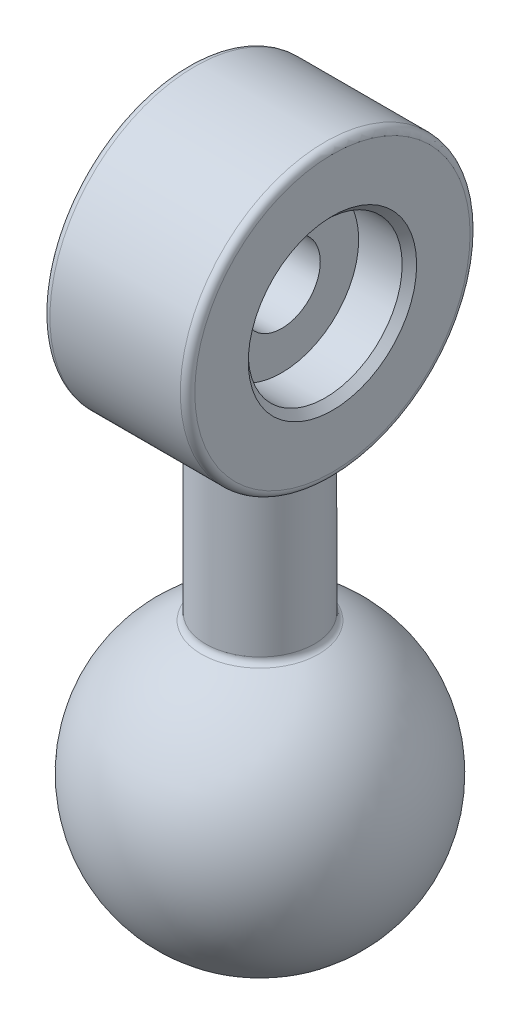
SolidWorks part; units mm, degrees
material "ABS"
ref_plane "Front Plane" through (0, 0, 0) normal (0, 0, 1) x (1, 0, 0)
ref_plane "Top Plane" through (0, 0, 0) normal (0, 1, 0) x (1, 0, 0)
ref_plane "Right Plane" through (0, 0, 0) normal (1, 0, 0) x (0, 0, -1)
sketch "Sketch1" plane through (0, 0, 0) normal (0, 0, 1) x (1, 0, 0)
  line L0 (0, 12.7) -> (0, -12.7)
  line L1 (0, 12.7) -> (0, 38.1)
  line L2 (0, 38.1) -> (-4.7625, 38.1)
  line L3 (-4.7625, 38.1) -> (-4.7625, 11.7732)
  arc A0 (0, -12.7) -> (0, 12.7) centre (0, 0) cw
  dimension "D1" = 25.4
  dimension "D2" = 25.4
  dimension "D3" = 4.7625
revolve "Revolve1" add sketch "Sketch1" angle 360 about L1
sketch "Sketch2" plane through (0, 0, 0) normal (1, 0, 0) x (0, 0, -1)
  line L1 (4.7625, 38.1) -> (-4.7625, 38.1) construction
  circle A3 centre (0, 38.1) radius 12.7
  dimension "D1" = 25.4
extrude "Boss-Extrude1" add sketch "Sketch2" along normal mid plane 12.7
fillet "Fillet1" radius 0.635 4 edges at (-4.7051, 25.4214, 0.7372) (6.35, 38.1, -12.7) (-6.35, 38.1, -12.7) (4.7625, 11.7732, 0)
hole_wizard "CBORE for 1/4 Pan Head Machine Screw1" positions "Sketch3" profile "Sketch4" counterbore size "1/4" standard "ANSI Inch" end condition through all
sketch "Sketch3" plane through (6.35, 0, 0) normal (1, 0, 0) x (0, 0, -1)
  point P0 (0, 38.1)
sketch "Sketch4" plane through (6.35, 38.1, 0) normal (0, 1, 0) x (0, 0, -1)
  line L0 (0, 0) -> (0, 19.05)
  line L1 (0, 19.05) -> (3.3782, 19.05)
  line L3 (3.3782, 19.05) -> (3.3782, 4.445)
  line L4 (6.7462, 4.445) -> (3.3782, 4.445)
  line L5 (6.7462, 4.445) -> (6.7462, 0.635)
  line L6 (6.7462, 0.635) -> (7.3812, 0)
  line L7 (7.3812, 0) -> (0, 0)
  line L8 (-6.7462, 0.635) -> (-7.3812, 0) construction
  line L11 (0, -6.35) -> (0, 107.95) construction
  dimension "Thru Hole Dia." = 6.7564
  dimension "Thru Hole Depth" = 19.05
  dimension "C'Bore Dia." = 13.4925
  dimension "C'Bore Depth" = 4.445
  dimension "Near C'Sink Dia." = 14.7625
  dimension "Near C'Sink Angle" = 90
